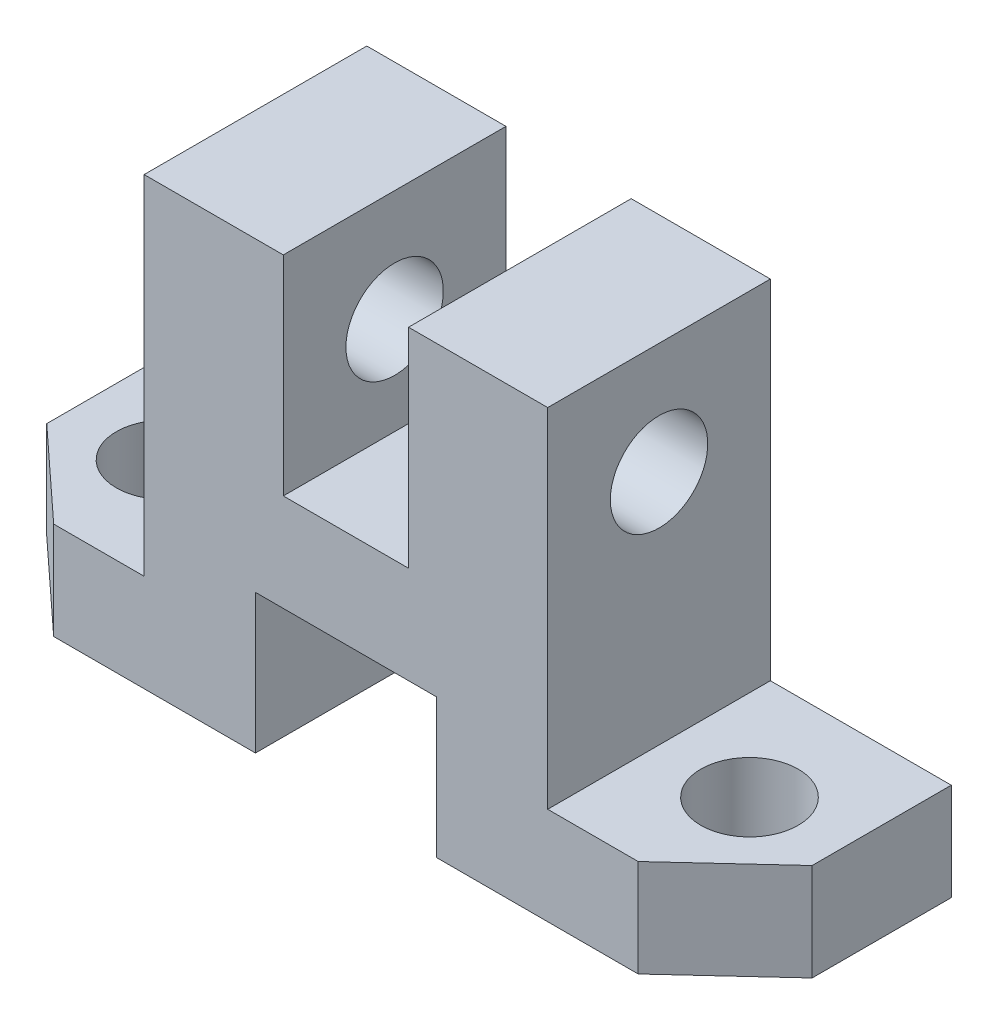
SolidWorks part; units mm, degrees
ref_plane "Front Plane" through (0, 0, 0) normal (0, 0, 1) x (1, 0, 0)
ref_plane "Top Plane" through (0, 0, 0) normal (0, 1, 0) x (1, 0, 0)
ref_plane "Right Plane" through (0, 0, 0) normal (1, 0, 0) x (0, 0, -1)
sketch "Sketch3" plane through (0, 0, 0) normal (0, 0, 1) x (1, 0, 0)
  line L0 (0, 0) -> (21, 0)
  line L1 (21, 0) -> (21, 10)
  line L2 (21, 10) -> (34, 10)
  line L3 (34, 10) -> (34, 0)
  line L4 (34, 0) -> (55, 0)
  line L5 (0, 0) -> (0, 7)
  line L6 (0, 7) -> (13, 7)
  line L7 (13, 7) -> (13, 32)
  line L8 (13, 32) -> (23, 32)
  line L9 (23, 32) -> (23, 17)
  line L10 (23, 17) -> (32, 17)
  line L11 (32, 17) -> (32, 32)
  line L12 (32, 32) -> (42, 32)
  line L13 (42, 32) -> (42, 7)
  line L14 (42, 7) -> (55, 7)
  line L15 (55, 7) -> (55, 0)
  dimension "D1" = 55
  dimension "D2" = 13
  dimension "D3" = 10
  dimension "D4" = 9
  dimension "D5" = 13
  dimension "D6" = 32
  dimension "D7" = 7
  dimension "D8" = 10
  dimension "D9" = 7
extrude "Boss-Extrude1" add sketch "Sketch3" along normal blind 16
sketch "Sketch8" plane through (0, 7, 0) normal (0, 1, 0) x (1, 0, 0)
  line L0 (0, -16) -> (0, 0) construction
  line L1 (13, 0) -> (0, 0) construction
  circle A0 centre (6.5, -8) radius 3.5
  point P6 (1.4546, -8.5124)
  dimension "D1" = 7
  dimension "D2" = 6.5
  dimension "D3" = 8
extrude "Cut-Extrude1" cut sketch "Sketch8" against normal blind 16
sketch "Sketch11" plane through (0, 7, 0) normal (0, 1, 0) x (1, 0, 0)
  line L0 (55, 0) -> (42, 0) construction
  line L1 (55, -16) -> (55, 0) construction
  circle A0 centre (48.5, -8) radius 3.5
  dimension "D1" = 7
  dimension "D2" = 8
  dimension "D3" = 6.5
extrude "Cut-Extrude2" cut sketch "Sketch11" against normal blind 16
sketch "Sketch12" plane through (13, 0, 0) normal (-1, 0, 0) x (0, 0, 1)
  line L0 (16, 32) -> (16, 7) construction
  line L1 (16, 32) -> (0, 32) construction
  circle A0 centre (8, 24) radius 3.5
  dimension "D1" = 7
  dimension "D2" = 8
  dimension "D3" = 8
extrude "Cut-Extrude3" cut sketch "Sketch12" against normal through all both and the other way through all
sketch "Sketch13" plane through (0, 7, 0) normal (0, 1, 0) x (1, 0, 0)
  line L0 (13, -16) -> (0, -16) construction
  line L1 (0, -16) -> (0, 0) construction
  line L2 (6.5, -16) -> (0, -16)
  line L3 (0, -16) -> (0, -10)
  line L4 (0, -10) -> (6.5, -16)
  dimension "D1" = 10
  dimension "D2" = 6.5
extrude "Cut-Extrude4" cut sketch "Sketch13" against normal through all both contours L4 L2 L3
sketch "Sketch14" plane through (0, 7, 0) normal (0, 1, 0) x (1, 0, 0)
  line L0 (55, -16) -> (55, 0) construction
  line L1 (55, -16) -> (42, -16) construction
  line L2 (55, -16) -> (55, -10)
  line L3 (55, -16) -> (48.5, -16)
  line L4 (48.5, -16) -> (55, -10)
  dimension "D1" = 6.5
  dimension "D2" = 6
extrude "Cut-Extrude5" cut sketch "Sketch14" against normal through all both
